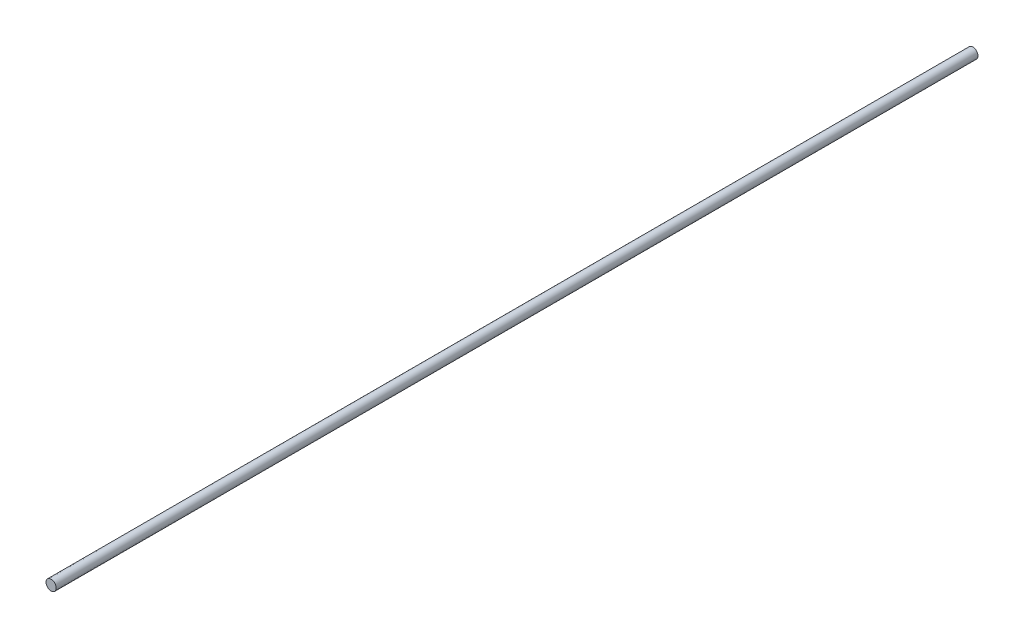
SolidWorks part; units mm, degrees
ref_plane "Plan de face" through (0, 0, 0) normal (0, 0, 1) x (1, 0, 0)
ref_plane "Plan de dessus" through (0, 0, 0) normal (0, 1, 0) x (1, 0, 0)
ref_plane "Plan de droite" through (0, 0, 0) normal (1, 0, 0) x (0, 0, -1)
sketch "Esquisse1" plane through (0, 0, 0) normal (0, 0, 1) x (1, 0, 0)
  circle A0 centre (0, 0) radius 5
  dimension "D1" = 10
extrude "Boss.-Extru.1" add sketch "Esquisse1" along normal blind 900
